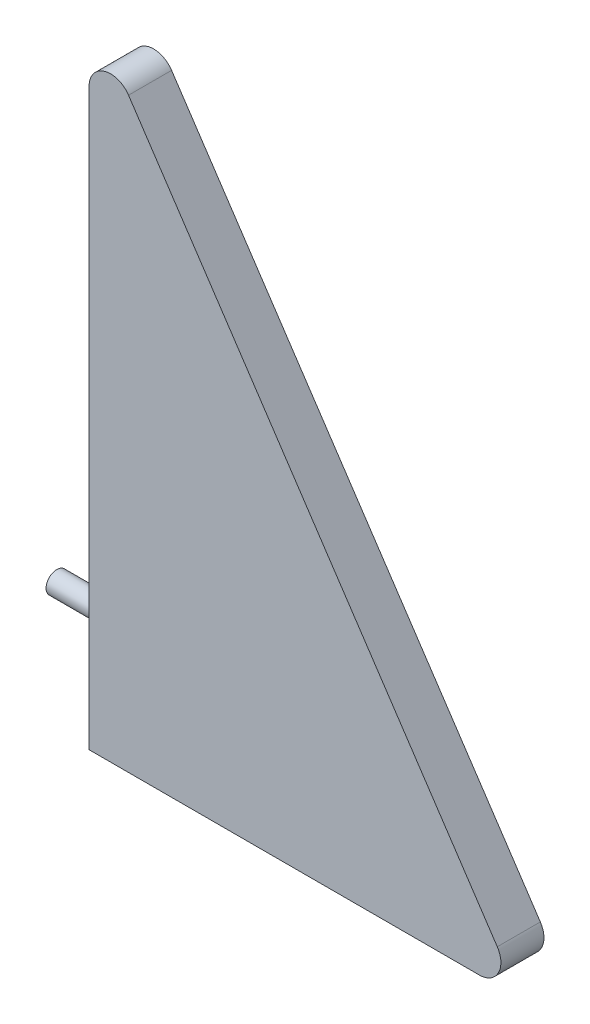
SolidWorks part; units mm, degrees
ref_plane "Front Plane" through (0, 0, 0) normal (0, 0, 1) x (1, 0, 0)
ref_plane "Top Plane" through (0, 0, 0) normal (0, 1, 0) x (1, 0, 0)
ref_plane "Right Plane" through (0, 0, 0) normal (1, 0, 0) x (0, 0, -1)
sketch "Sketch1" plane through (0, 0, 0) normal (0, 0, 1) x (1, 0, 0)
  line L0 (0, 0) -> (1813.1483, 0)
  line L1 (1896.3533, 155.47) -> (183.205, 2725.1925)
  line L2 (0, 2669.7224) -> (0, 0)
  arc A0 (183.205, 2725.1925) -> (0, 2669.7224) centre (100, 2669.7224) ccw
  arc A1 (1813.1483, 0) -> (1896.3533, 155.47) centre (1813.1483, 100) ccw
  point P6 (0, 3000)
  point P9 (2000, 0)
  dimension "D3" = 100
  dimension "D4" = 100
  dimension "D1" = 3000
  dimension "D2" = 2000
extrude "Boss-Extrude1" add sketch "Sketch1" along normal blind 200
sketch "Sketch2" plane through (0, 0, 0) normal (-1, 0, 0) x (0, 0, 1)
  line L0 (200, 0) -> (0, 0) construction
  circle A0 centre (100, 500) radius 50
  dimension "D2" = 100
  dimension "D1" = 500
  dimension "D3" = 100
extrude "Boss-Extrude2" add sketch "Sketch2" along normal blind 250
